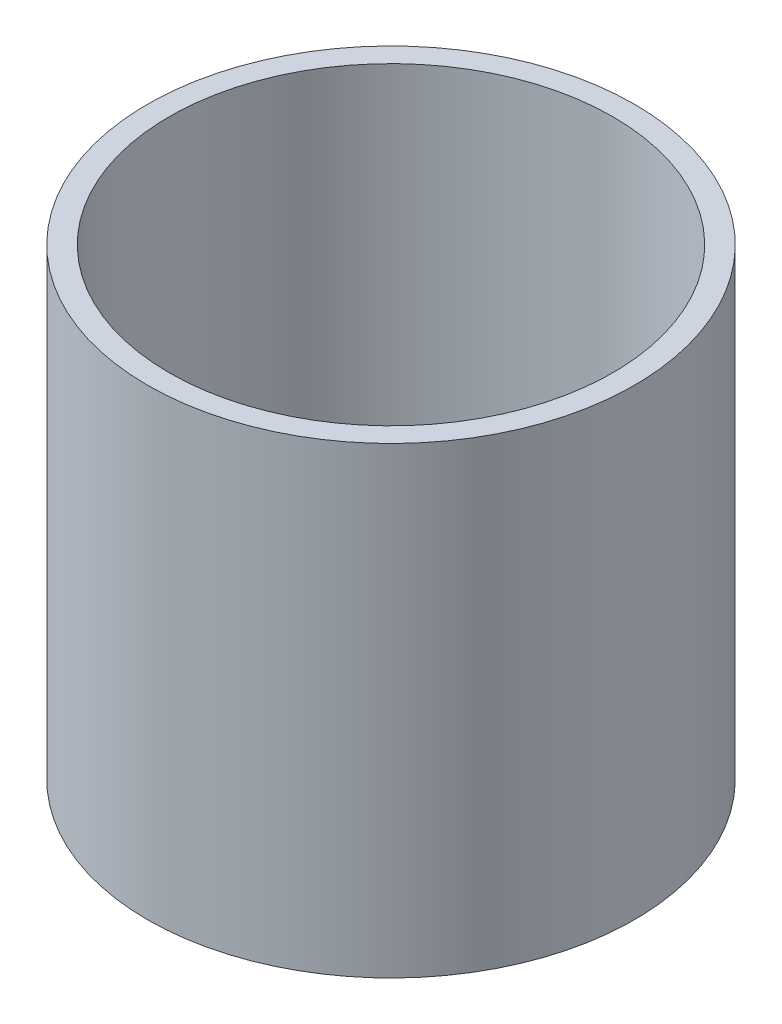
SolidWorks part; units mm, degrees
ref_plane "Front Plane" through (0, 0, 0) normal (0, 0, 1) x (1, 0, 0)
ref_plane "Top Plane" through (0, 0, 0) normal (0, 1, 0) x (1, 0, 0)
ref_plane "Right Plane" through (0, 0, 0) normal (1, 0, 0) x (0, 0, -1)
sketch "Sketch1" plane through (0, 0, 0) normal (0, 1, 0) x (1, 0, 0)
  circle A0 centre (0, 0) radius 31.55
  dimension "D1" = 63.1
extrude "Boss-Extrude1" add sketch "Sketch1" along normal blind 10
sketch "Sketch3" plane through (0, 10, 0) normal (0, 1, 0) x (1, 0, 0)
  line L0 (-18.765, 0) -> (18.765, 0) construction
  line L1 (-5.5, 0) -> (5.5, 0) construction
  circle A0 centre (-18.765, 0) radius 4.15
  circle A1 centre (18.765, 0) radius 4.15
  circle A4 centre (0, 0) radius 31.55 construction
  point P3 (0, 0)
  point P6 (0, 0)
  dimension "D2" = 8.3
  dimension "D3" = 8.3
  dimension "D1" = 37.53
  dimension "D4" = 0
extrude "Cut-Extrude1" cut sketch "Sketch3" against normal blind 10
sketch "Sketch5" plane through (0, 10, 0) normal (0, 1, 0) x (1, 0, 0)
  circle A0 centre (0, 0) radius 28.75
  circle A1 centre (0, 0) radius 31.55
  dimension "D1" = 63.1
  dimension "D2" = 2.8
extrude "Boss-Extrude2" add sketch "Sketch5" along normal blind 50
